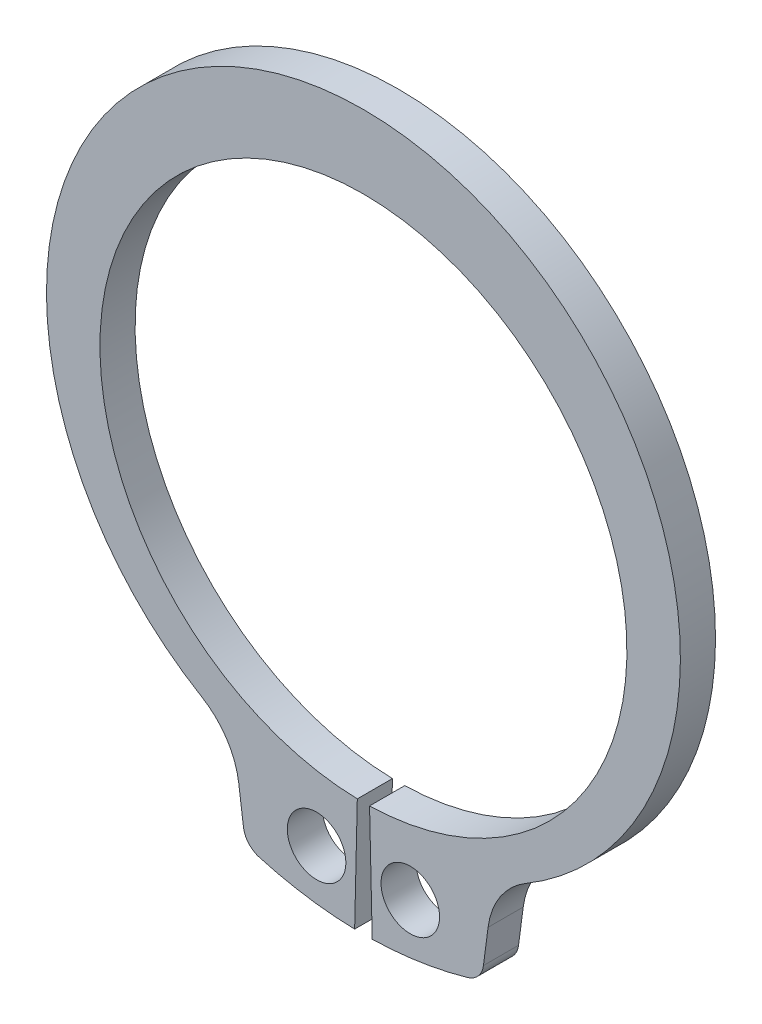
SolidWorks part; units mm, degrees
ref_plane "Plane1" through (0, 0, 0) normal (0, 0, 1) x (1, 0, 0)
ref_plane "Plane2" through (0, 0, 0) normal (0, 1, 0) x (1, 0, 0)
ref_plane "Plane3" through (0, 0, 0) normal (1, 0, 0) x (0, 0, -1)
sketch "Clipboard" plane through (0, 0, 0) normal (0, 0, 1) x (1, 0, 0)
  line L0 (0, 0) -> (2.5, 0)
  line L1 (0, 0) -> (0, 1.25)
  line L2 (0, 0) -> (0, -3.9)
  circle A0 centre (0, 0) radius 1
  circle A1 centre (0, 0) radius 9.5
  dimension "HoleDia" = 2
  dimension "ShaftDia" = 19
  dimension "LargeSection" = 2.5
  dimension "SmallSection" = 1.25
  dimension "LugSection" = 3.9
sketch "BodySke" plane through (0, 0, 0) normal (0, 0, 1) x (1, 0, 0)
  line L0 (-1.5431, 0) -> (1.5431, 0) construction
  line L1 (0, 0) -> (0, 11.5) construction
  line L2 (0.2093, -8.9976) -> (0.3, -12.8965)
  line L3 (-0.2093, -8.9976) -> (-0.3, -12.8965)
  line L4 (0, 0) -> (6.884, -10.9097) construction
  line L5 (0, 0) -> (-6.884, -10.9097) construction
  line L7 (4.2578, -10.5639) -> (4.0983, -11.7756)
  line L8 (-4.2578, -10.5639) -> (-4.0983, -11.7756)
  circle A0 centre (0, 0) radius 9 construction
  arc A1 (0.2093, -8.9976) -> (-0.2093, -8.9976) centre (0, 0) ccw
  arc A2 (5.4698, -8.6685) -> (-5.4698, -8.6685) centre (0, 0.674) ccw construction
  arc A3 (0.3, -12.8965) -> (3.5618, -12.3985) centre (0, 0) ccw
  arc A4 (5.5308, -8.6326) -> (4.2578, -10.5639) centre (6.884, -10.9097) ccw
  arc A5 (-4.2578, -10.5639) -> (-5.5308, -8.6326) centre (-6.884, -10.9097) ccw
  arc A6 (-3.5618, -12.3985) -> (-0.3, -12.8965) centre (0, 0) ccw
  arc A7 (5.5308, -8.6326) -> (-5.5308, -8.6326) centre (0, 0.674) ccw
  arc A8 (-4.2863, -10.3473) -> (4.2863, -10.3473) centre (0, 0) ccw construction
  circle A9 centre (1.6, -11.0851) radius 1
  circle A10 centre (-1.6, -11.0851) radius 1
  arc A11 (4.0983, -11.7756) -> (3.5618, -12.3985) centre (3.3547, -11.6777) cw
  arc A12 (-4.0983, -11.7756) -> (-3.5618, -12.3985) centre (-3.3547, -11.6777) ccw
  point P28 (4.0355, -12.2525)
  point P31 (-4.0355, -12.2525)
  dimension "GrooveDia" = 18
  dimension "D3" = 0.75
  dimension "LugRad" = 12.9
  dimension "HoleOffsetRad" = 11.2
  dimension "HoleDia" = 2
  dimension "D2" = 15
  dimension "LargeRad" = 11.5
  dimension "SmallRad" = 10.25
  dimension "Gap" = 0.6
  dimension "SmallAngle" = 64.504
  dimension "HoleSpacing" = 3.2
extrude "Body" add sketch "BodySke" against normal blind 1.2
sketch "NotSke" plane through (0, 0, 0) normal (0, 0, 1) x (1, 0, 0)
  line L0 (1.6, -10.0851) -> (1.6, -12.0851)
  line L1 (1.6, -12.0851) -> (-1.6, -12.0851)
  line L2 (-1.6, -12.0851) -> (-1.6, -10.0851)
  line L3 (-1.6, -10.0851) -> (1.6, -10.0851)
  circle A0 centre (1.6, -11.0851) radius 1 construction
  circle A1 centre (-1.6, -11.0851) radius 1 construction
extrude "Notch" [suppressed] cut sketch "NotSke" against normal through all
sketch "UnlSke" plane through (0, 0, 0) normal (0, 0, 1) x (1, 0, 0)
  line L0 (-2.9755, -12.5522) -> (-2.0759, -8.7573)
  line L1 (2.9755, -12.5522) -> (2.0759, -8.7573)
  arc A0 (2.0759, -8.7573) -> (-2.0759, -8.7573) centre (0, 0) ccw
  arc A1 (2.9755, -12.5522) -> (-2.9755, -12.5522) centre (0, 0) ccw
  arc A2 (0.3, -12.8965) -> (3.5618, -12.3985) centre (0, 0) ccw construction
  arc A3 (0.2093, -8.9976) -> (-0.2093, -8.9976) centre (0, 0) ccw construction
  circle A4 centre (-1.6, -11.0851) radius 1 construction
  circle A5 centre (1.6, -11.0851) radius 1 construction
extrude "Unlug" [suppressed] add sketch "UnlSke" against normal through all
equation "' \"ShaftDia@Clipboard\" = 3"
equation "' \"Thickness@Body\" = 0.4"
equation "' \"GrooveDia@BodySke\" = 2.8"
equation "' \"LugSection@Clipboard\" = 1.9"
equation "' \"LargeSection@Clipboard\" = 0.8"
equation "' \"HoleDia@Clipboard\" = 1.0"
equation "' \"ShaftDia@Clipboard\" = 10"
equation "' \"Thickness@Body\" = 1.0"
equation "' \"GrooveDia@BodySke\" = 9.6"
equation "' \"LugSection@Clipboard\" = 3.3"
equation "' \"LargeSection@Clipboard\" = 1.8"
equation "' \"HoleDia@Clipboard\" = 1.5"
equation "\"SmallSection@Clipboard\" = \"LargeSection@Clipboard\" * 0.5"
equation "\"Gap@BodySke\" =  \"Thickness@Body\" / 2"
equation "\"LargeRad@BodySke\" =  \"GrooveDia@BodySke\" / 2 +  \"LargeSection@Clipboard\""
equation "\"SmallRad@BodySke\" =  \"GrooveDia@BodySke\" / 2 +  \"SmallSection@Clipboard\""
equation "\"LugRad@BodySke\" = \"GrooveDia@BodySke\" / 2 + \"LugSection@Clipboard\""
equation "\"HoleOffsetRad@BodySke\" = (  \"ShaftDia@Clipboard\" / 2 + \"LugRad@BodySke\" ) / 2"
equation "\"HoleSpacing@BodySke\" = \"Gap@BodySke\"  * 2 +  \"HoleDia@Clipboard\""
equation "\"HoleDia@BodySke\" =  \"HoleDia@Clipboard\""
equation "\"SmallAngle@BodySke\" = atn(\"HoleSpacing@BodySke\" / 2 / sqr(\"HoleOffsetRad@BodySke\"  * \"HoleOffsetRad@BodySke\" - (\"HoleSpacing@BodySke\" / 2) * (\"HoleSpacing@BodySke\" / 2) ))  * 7 *  (\"LargeRad@BodySke\" / \"SmallRad@BodySke\")* ( 180 / 3.141593)"
